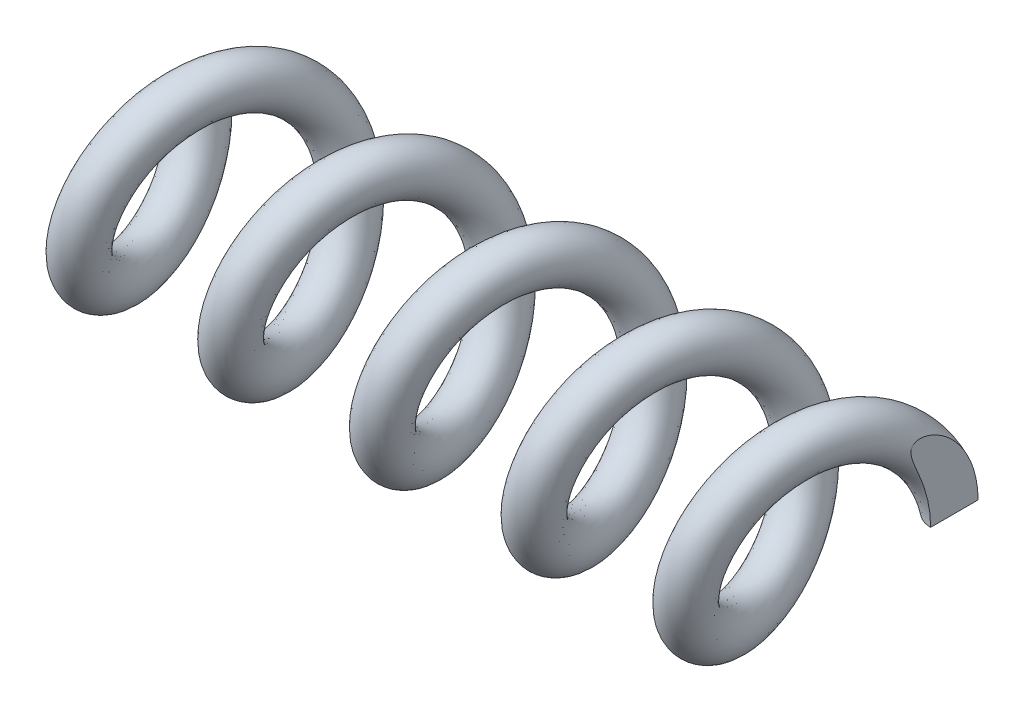
SolidWorks part; units mm, degrees
ref_plane "Front Plane" through (0, 0, 0) normal (0, 0, 1) x (1, 0, 0)
ref_plane "Top Plane" through (0, 0, 0) normal (0, 1, 0) x (1, 0, 0)
ref_plane "Right Plane" through (0, 0, 0) normal (1, 0, 0) x (0, 0, -1)
sketch "Sketch1" plane through (0, 0, 0) normal (1, 0, 0) x (0, 0, -1)
  circle A0 centre (0, 0) radius 4
curve "Helix/Spiral1" pitch 6.4 height 32 turns 5
sketch "Sketch4" plane through (0, 0, 0) normal (0, 1, 0) x (1, 0, 0)
  line L0 (0, 0) -> (0, 4) construction
  circle A0 centre (0, 4) radius 1
  spline S0 degree 3 poles (242.2976, -1980.7805) (-14.8831, -247.891) (-6.5596, 19.2902) (0.7999, 2.9021) (1.2, 1.5706) (1.6, 0) (2, -1.5706) (2.4, -2.9021) (2.8, -3.7917) (3.2, -4.1041) (3.6, -3.7917) (4, -2.9021) (4.4, -1.5706) (4.8, 0) (5.2, 1.5706) (5.6, 2.9021) (6, 3.7917) (6.4, 4.1041) (6.8, 3.7917) (7.2, 2.9021) (7.6, 1.5706) (8, 0) (8.4, -1.5706) (8.8, -2.9021) (9.2, -3.7917) (9.6, -4.1041) (10, -3.7917) (10.4, -2.9021) (10.8, -1.5706) (11.2, 0) (11.6, 1.5706) (12, 2.9021) (12.4, 3.7917) (12.8, 4.1041) (13.2, 3.7917) (13.6, 2.9021) (14, 1.5706) (14.4, 0) (14.8, -1.5706) (15.2, -2.9021) (15.6, -3.7917) (16, -4.1041) (16.4, -3.7917) (16.8, -2.9021) (17.2, -1.5706) (17.6, 0) (18, 1.5706) (18.4, 2.9021) (18.8, 3.7917) (19.2, 4.1041) (19.6, 3.7917) (20, 2.9021) (20.4, 1.5706) (20.8, 0) (21.2, -1.5706) (21.6, -2.9021) (22, -3.7917) (22.4, -4.1041) (22.8, -3.7917) (23.2, -2.9021) (23.6, -1.5706) (24, 0) (24.4, 1.5706) (24.8, 2.9021) (25.2, 3.7917) (25.6, 4.1041) (26, 3.7917) (26.4, 2.9021) (26.8, 1.5706) (27.2, 0) (27.6, -1.5706) (28, -2.9021) (28.4, -3.7917) (28.8, -4.1041) (29.2, -3.7917) (29.6, -2.9021) (30, -1.5706) (30.4, 0) (30.8, 1.5706) (31.2001, 2.9021) (38.5596, 19.2902) (46.8831, -247.8923) (-210.2995, -1980.7932) knots -0.653272 -0.653272 -0.653272 -0.653272 0.0125 0.025 0.0375 0.05 0.0625 0.075 0.0875 0.1 0.1125 0.125 0.1375 0.15 0.1625 0.175 0.1875 0.2 0.2125 0.225 0.2375 0.25 0.2625 0.275 0.2875 0.3 0.3125 0.325 0.3375 0.35 0.3625 0.375 0.3875 0.4 0.4125 0.425 0.4375 0.45 0.4625 0.475 0.4875 0.5 0.5125 0.525 0.5375 0.55 0.5625 0.575 0.5875 0.6 0.6125 0.625 0.6375 0.65 0.6625 0.675 0.6875 0.7 0.7125 0.725 0.7375 0.75 0.7625 0.775 0.7875 0.8 0.8125 0.825 0.8375 0.85 0.8625 0.875 0.8875 0.9 0.9125 0.925 0.9375 0.95 0.9625 0.975 0.9875 1.653273 1.653273 1.653273 1.653273 only from (0, 4) to (32, 4) construction
  spline S1 degree 3 poles (0, 4) (0.1325, 4) (0.4004, 3.7917) (0.7999, 2.9021) (1.2, 1.5706) (1.6, 0) (2, -1.5706) (2.4, -2.9021) (2.8, -3.7917) (3.2, -4.1041) (3.6, -3.7917) (4, -2.9021) (4.4, -1.5706) (4.8, 0) (5.2, 1.5706) (5.6, 2.9021) (6, 3.7917) (6.4, 4.1041) (6.8, 3.7917) (7.2, 2.9021) (7.6, 1.5706) (8, 0) (8.4, -1.5706) (8.8, -2.9021) (9.2, -3.7917) (9.6, -4.1041) (10, -3.7917) (10.4, -2.9021) (10.8, -1.5706) (11.2, 0) (11.6, 1.5706) (12, 2.9021) (12.4, 3.7917) (12.8, 4.1041) (13.2, 3.7917) (13.6, 2.9021) (14, 1.5706) (14.4, 0) (14.8, -1.5706) (15.2, -2.9021) (15.6, -3.7917) (16, -4.1041) (16.4, -3.7917) (16.8, -2.9021) (17.2, -1.5706) (17.6, 0) (18, 1.5706) (18.4, 2.9021) (18.8, 3.7917) (19.2, 4.1041) (19.6, 3.7917) (20, 2.9021) (20.4, 1.5706) (20.8, 0) (21.2, -1.5706) (21.6, -2.9021) (22, -3.7917) (22.4, -4.1041) (22.8, -3.7917) (23.2, -2.9021) (23.6, -1.5706) (24, 0) (24.4, 1.5706) (24.8, 2.9021) (25.2, 3.7917) (25.6, 4.1041) (26, 3.7917) (26.4, 2.9021) (26.8, 1.5706) (27.2, 0) (27.6, -1.5706) (28, -2.9021) (28.4, -3.7917) (28.8, -4.1041) (29.2, -3.7917) (29.6, -2.9021) (30, -1.5706) (30.4, 0) (30.8, 1.5706) (31.2001, 2.9021) (31.5996, 3.7917) (31.8675, 4) (32, 4) knots 0 0 0 0 0.0125 0.025 0.0375 0.05 0.0625 0.075 0.0875 0.1 0.1125 0.125 0.1375 0.15 0.1625 0.175 0.1875 0.2 0.2125 0.225 0.2375 0.25 0.2625 0.275 0.2875 0.3 0.3125 0.325 0.3375 0.35 0.3625 0.375 0.3875 0.4 0.4125 0.425 0.4375 0.45 0.4625 0.475 0.4875 0.5 0.5125 0.525 0.5375 0.55 0.5625 0.575 0.5875 0.6 0.6125 0.625 0.6375 0.65 0.6625 0.675 0.6875 0.7 0.7125 0.725 0.7375 0.75 0.7625 0.775 0.7875 0.8 0.8125 0.825 0.8375 0.85 0.8625 0.875 0.8875 0.9 0.9125 0.925 0.9375 0.95 0.9625 0.975 0.9875 1 1 1 1
sweep "Sweep1" add profiles "Sketch4" path "Helix/Spiral1"
sketch "Sketch5" plane through (0, 0, 0) normal (0, 1, 0) x (1, 0, 0)
  line L0 (0, 5) -> (0, 4) construction
  line L2 (0, 5) -> (-3.2632, 5)
  line L3 (0, 5) -> (0, -2.5447)
  line L4 (0, -2.5447) -> (-3.2632, -2.5447)
  line L5 (-3.2632, 5) -> (-3.2632, -2.5447)
  circle A0 centre (0, 4) radius 1 construction
extrude "Cut-Extrude1" cut sketch "Sketch5" against normal blind 10
sketch "Sketch6" plane through (0, 0, 0) normal (0, -1, 0) x (1, 0, 0)
  line L0 (32, -4) -> (32, -5) construction
  line L2 (32, -5) -> (35.1738, -5)
  line L3 (32, -5) -> (32, 1.1757)
  line L4 (32, 1.1757) -> (35.1738, 1.1757)
  line L5 (35.1738, -5) -> (35.1738, 1.1757)
  circle A0 centre (32, -4) radius 1 construction
extrude "Cut-Extrude2" cut sketch "Sketch6" against normal blind 10
